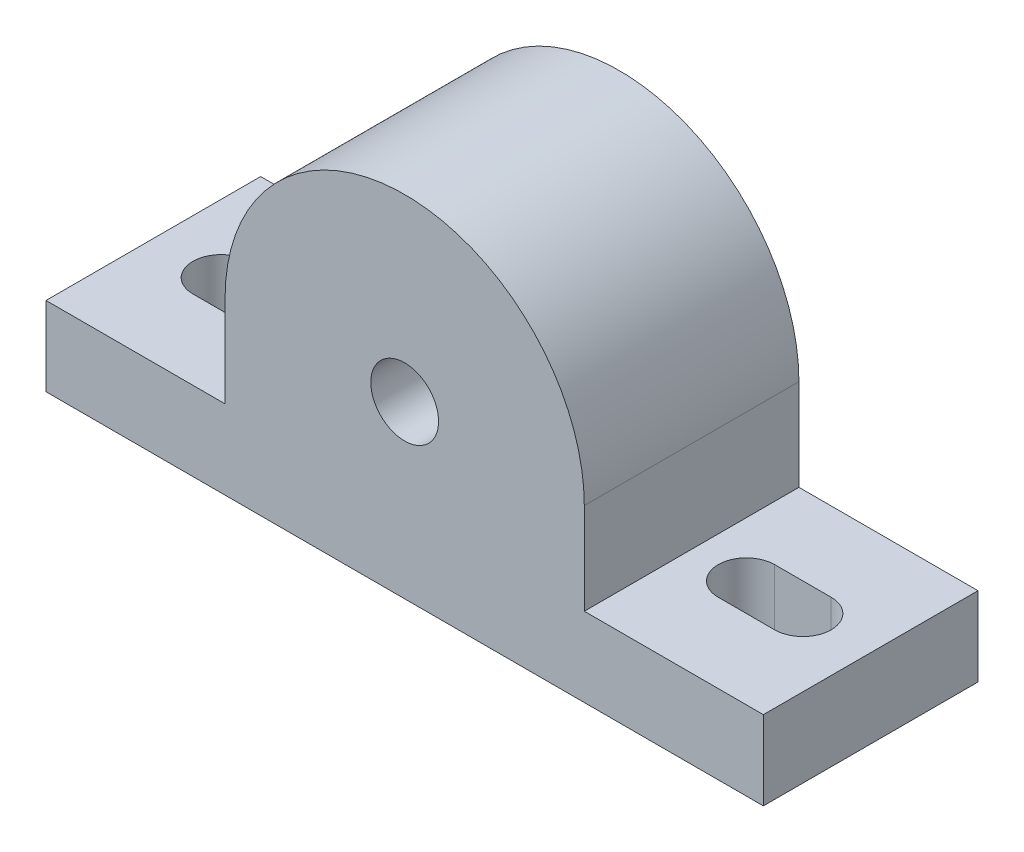
SolidWorks part; units mm, degrees
material "Нержавеющая сталь (ферритная)"
ref_plane "Спереди (XY)" through (0, 0, 0) normal (0, 0, 1) x (1, 0, 0)
ref_plane "Сверху (XZ)" through (0, 0, 0) normal (0, 1, 0) x (1, 0, 0)
ref_plane "Справа (ZY)" through (0, 0, 0) normal (1, 0, 0) x (0, 0, -1)
sketch "Эскиз1" plane through (0, 0, 0) normal (0, 0, 1) x (1, 0, 0)
  line L0 (-31.8, 0) -> (-31.8, 16.2)
  line L1 (-31.8, 0) -> (-63.5, 0)
  line L2 (-63.5, 0) -> (-63.5, -14)
  line L3 (-63.5, -14) -> (63.5, -14)
  line L4 (0, 57.8007) -> (0, -15.8842) construction
  line L5 (31.8, 0) -> (63.5, 0)
  line L6 (63.5, 0) -> (63.5, -14)
  line L7 (31.8, 0) -> (31.8, 16.2)
  arc A0 (-31.8, 16.2) -> (31.8, 16.2) centre (0, 16.2) cw
  circle A1 centre (0, 16.2) radius 6
  point P3 (0, 48)
  point P14 (0, -14)
  dimension "D1" = 12
  dimension "D2" = 62
  dimension "D3" = 30.2
  dimension "D4" = 127
  dimension "D5" = 14
extrude "Бобышка-Вытянуть1" add sketch "Эскиз1" along normal mid plane 38
sketch "Эскиз2" plane through (0, 0, 0) normal (0, 1, 0) x (1, 0, 0)
  line L0 (0, -33.2051) -> (0, 42.8392) construction
  line L1 (55.9476, 0) -> (-72.43, 0) construction
  line L2 (-51.5, 0) -> (-41.5, 0) construction
  line L3 (-51.5, 5) -> (-41.5, 5)
  line L4 (-51.5, -5) -> (-41.5, -5)
  line L5 (-63.5, -19) -> (-63.5, 19) construction
  line L6 (51.5, 0) -> (41.5, 0) construction
  line L7 (51.5, 5) -> (41.5, 5)
  line L8 (51.5, -5) -> (41.5, -5)
  arc A0 (-51.5, 5) -> (-51.5, -5) centre (-51.5, 0) ccw
  arc A1 (-41.5, -5) -> (-41.5, 5) centre (-41.5, 0) ccw
  arc A2 (51.5, 5) -> (51.5, -5) centre (51.5, 0) cw
  arc A3 (41.5, -5) -> (41.5, 5) centre (41.5, 0) cw
  point P7 (-46.5, 0)
  point P16 (46.5, 0)
  dimension "D1" = 12
  dimension "D2" = 10
  dimension "D3" = 10
extrude "Вырез-Вытянуть1" cut sketch "Эскиз2" against normal through all
